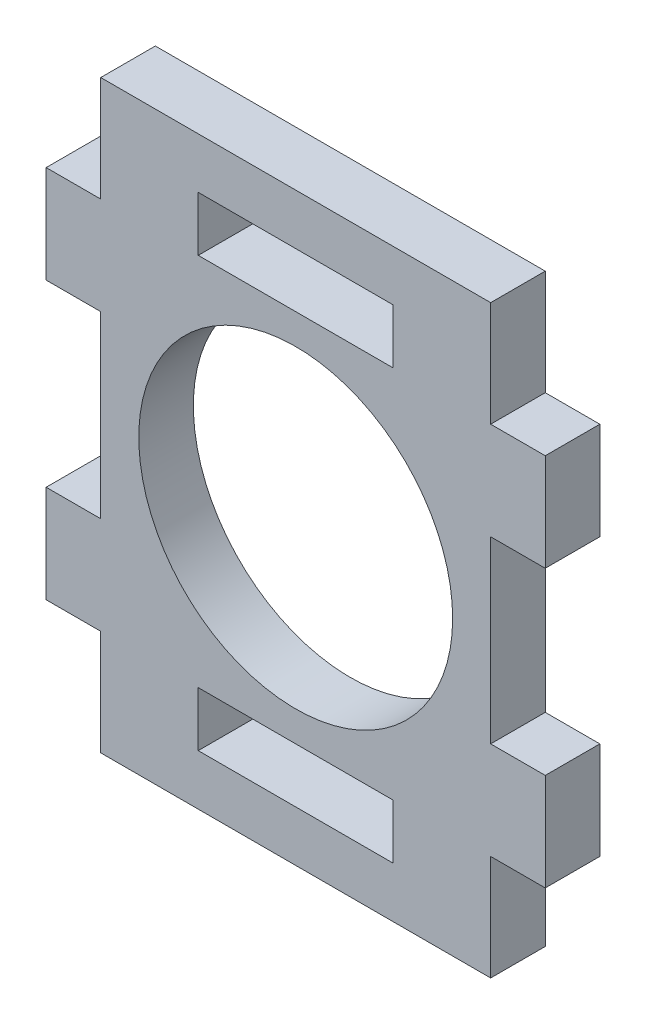
SolidWorks part; units mm, degrees
material "Фанера"
ref_plane "Front Plane" through (0, 0, 0) normal (0, 0, 1) x (1, 0, 0)
ref_plane "Top Plane" through (0, 0, 0) normal (0, 1, 0) x (1, 0, 0)
ref_plane "Right Plane" through (0, 0, 0) normal (1, 0, 0) x (0, 0, -1)
sketch "Эскиз1" plane through (0, 0, 0) normal (0, 0, 1) x (1, 0, 0)
  line L0 (-10, 9.6) -> (-12.8, 9.6)
  line L1 (-10, -15) -> (10, -15)
  line L2 (-10, -15) -> (-10, -9.6)
  line L3 (-10, 15) -> (10, 15)
  line L4 (10, -15) -> (10, -9.6)
  line L5 (-10, -15) -> (10, 15) construction
  line L6 (-10, 15) -> (10, -15) construction
  line L7 (-12.8, 9.6) -> (-12.8, 4.6)
  line L8 (-12.8, 4.6) -> (-10, 4.6)
  line L9 (-24.8552, 0) -> (28.9627, 0) construction
  line L10 (0, 23.0741) -> (0, -18.911) construction
  line L11 (-10, 9.6) -> (-10, 15)
  line L12 (12.8, 4.6) -> (10, 4.6)
  line L13 (12.8, 9.6) -> (12.8, 4.6)
  line L14 (10, 9.6) -> (12.8, 9.6)
  line L15 (10, 9.6) -> (10, 15)
  line L16 (10, -9.6) -> (12.8, -9.6)
  line L17 (12.8, -9.6) -> (12.8, -4.6)
  line L18 (12.8, -4.6) -> (10, -4.6)
  line L19 (-12.8, -4.6) -> (-10, -4.6)
  line L20 (-12.8, -9.6) -> (-12.8, -4.6)
  line L21 (-10, -9.6) -> (-12.8, -9.6)
  line L22 (-10, -4.6) -> (-10, 4.6)
  line L23 (10, -4.6) -> (10, 4.6)
  line L24 (5, -12.4) -> (-5, -12.4)
  line L25 (5, 9.6) -> (-5, 9.6)
  line L26 (5, 9.6) -> (5, 12.4)
  line L27 (5, 12.4) -> (-5, 12.4)
  line L28 (-5, 9.6) -> (-5, 12.4)
  line L29 (5, 9.6) -> (-5, 12.4) construction
  line L30 (5, 12.4) -> (-5, 9.6) construction
  line L31 (-5, -9.6) -> (-5, -12.4)
  line L32 (5, -9.6) -> (-5, -9.6)
  line L33 (5, -9.6) -> (5, -12.4)
  circle A0 centre (0, 0) radius 8.05
  point P0 (0, 0)
  point P28 (0, 11)
  point P33 (0, 0)
  dimension "D2" = 16.1
  dimension "D1" = 20
  dimension "D3" = 30
  dimension "D4" = 5
  dimension "D5" = 2.8
  dimension "D6" = 5.4
  dimension "D7" = 10
  dimension "D8" = 2.8
  dimension "D9" = 2.6
extrude "Бобышка-Вытянуть1" add sketch "Эскиз1" along normal mid plane 2.8
